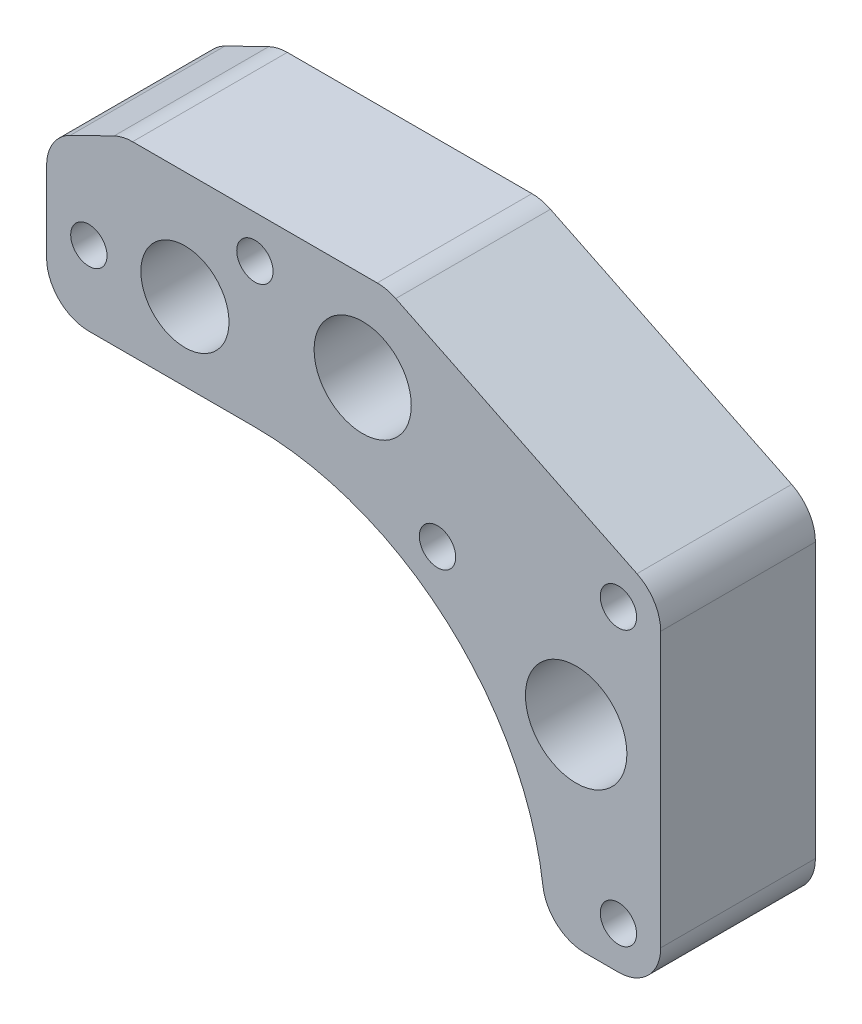
SolidWorks part; units mm, degrees
material "ABS"
ref_plane "前视基准面" through (0, 0, 0) normal (0, 0, 1) x (1, 0, 0)
ref_plane "上视基准面" through (0, 0, 0) normal (0, 1, 0) x (1, 0, 0)
ref_plane "右视基准面" through (0, 0, 0) normal (1, 0, 0) x (0, 0, -1)
other "Configuration Table"
sketch "草图1" plane through (0, 0, 0) normal (0, 0, 1) x (1, 0, 0)
  line L0 (0, 0) -> (0, 104) construction
  line L1 (0, 0) -> (-56, 0)
  line L2 (-56, 0) -> (-56, 56.65)
  line L4 (56, 56.65) -> (56, 0)
  line L5 (56, 0) -> (0, 0)
  line L6 (-56, 56.65) -> (-8.2819, 111.2395)
  line L7 (8.2819, 111.2395) -> (56, 56.65)
  arc A0 (34.35, 0) -> (-34.35, 0) centre (0, 0) ccw
  circle A1 centre (0, 104) radius 6
  arc A2 (8.2819, 111.2395) -> (-8.2819, 111.2395) centre (0, 104) ccw
  dimension "D1" = 68.7
  dimension "D3" = 12
  dimension "D7" = 5
  dimension "D2" = 104
  dimension "D4" = 112
  dimension "D5" = 56.65
  dimension "D6" = 56
extrude "凸台-拉伸1" add sketch "草图1" along normal blind 18.3
sketch "草图2" plane through (0, 0, 0) normal (0, 0, -1) x (-1, 0, 0)
  line L0 (56, 34.35) -> (0, 34.35)
  line L1 (56, 0) -> (56, 56.65) construction
  line L3 (56, 34.35) -> (56, 0)
  line L4 (56, 0) -> (34.35, 0)
  arc A0 (34.35, 0) -> (-34.35, 0) centre (0, 0) ccw construction
  arc A1 (34.35, 0) -> (0, 34.35) centre (0, 0) ccw
extrude "切除-拉伸1" cut sketch "草图2" against normal up to surface (18.3 mm away) up to face at (6, 104, 18.3)
sketch "草图3" plane through (0, 0, 0) normal (0, 0, -1) x (-1, 0, 0)
  line L0 (41, 34.35) -> (41, 59.35)
  line L1 (56, 34.35) -> (0, 34.35) construction
  line L2 (41, 59.35) -> (9.3178, 109.8462)
  line L3 (9.3178, 109.8462) -> (56, 56.65)
  line L4 (56, 56.65) -> (56, 34.35)
  line L5 (56, 34.35) -> (41, 34.35)
  arc A0 (8.2819, 111.2395) -> (-8.2819, 111.2395) centre (0, 104) ccw construction
  dimension "D1" = 15
  dimension "D2" = 25
extrude "切除-拉伸2" cut sketch "草图3" against normal up to surface (18.3 mm away) up to face at (5.183, 51.9192, 18.3)
sketch "草图4" plane through (0, 0, 18.3) normal (0, 0, 1) x (1, 0, 0)
  line L0 (-9.3178, 109.8462) -> (-8.855, 110.5838)
  line L1 (-56, 56.65) -> (-8.2819, 111.2395) construction
  line L10 (-56, 56.65) -> (-9.3178, 109.8462)
  line L11 (-9.3178, 109.8462) -> (-41, 59.35)
  line L12 (-41, 59.35) -> (-41, 34.35)
  line L13 (-41, 34.35) -> (0, 34.35)
  line L14 (34.35, 0) -> (56, 0)
  line L15 (56, 0) -> (56, 56.65)
  line L16 (56, 56.65) -> (8.2819, 111.2395)
  line L17 (-8.2819, 111.2395) -> (-56, 56.65)
  line L18 (-56, 56.65) -> (-9.3178, 109.8462)
  line L25 (-8.855, 110.5838) -> (-56, 56.65)
  arc A0 (8.2819, 111.2395) -> (-8.2819, 111.2395) centre (0, 104) ccw construction
  arc A3 (34.35, 0) -> (0, 34.35) centre (0, 0) ccw
  arc A4 (8.2819, 111.2395) -> (-8.2819, 111.2395) centre (0, 104) ccw
  dimension "D1" = 0
extrude "切除-拉伸3" cut sketch "草图4" against normal up to surface (18.3 mm away) up to face at (6, 104, 0)
fillet "圆角1" radius 2 1 edges at (-41, 34.35, 9.15)
sketch "草图5" plane through (0, 0, 0) normal (0, 0, -1) x (-1, 0, 0)
  line L1 (24.6418, 34.35) -> (24.6418, 85.4223)
  line L3 (39, 34.35) -> (0, 34.35) construction
  line L4 (24.6418, 34.35) -> (54.6418, 34.35)
  line L5 (54.6418, 34.35) -> (54.6418, 59.35)
  line L6 (54.6418, 59.35) -> (24.6418, 85.4223)
  line L8 (8.855, 110.5838) -> (41, 59.35) construction
  dimension "D1" = 24.6418
  dimension "D2" = 30
  dimension "D3" = 25
extrude "切除-拉伸4" cut sketch "草图5" against normal up to surface (18.3 mm away) up to face at (2.3195, 56.4573, 18.3)
sketch "草图6" plane through (0, 0, 18.3) normal (0, 0, 1) x (1, 0, 0)
  line L1 (54.3153, 37.4718) -> (15.6226, 56.3463) construction
  line L2 (-24.6418, 56.3463) -> (15.6226, 56.3463)
  line L3 (54.3153, 37.4718) -> (15.6226, 56.3463)
  line L4 (-24.6418, 85.4223) -> (-24.6418, 34.35) construction
  line L5 (-24.6418, 56.3463) -> (-24.6418, 119.4718)
  line L6 (-24.6418, 119.4718) -> (54.3153, 119.4718)
  line L7 (54.3153, 119.4718) -> (54.3153, 37.4718)
  line L8 (-24.6418, 34.35) -> (0, 34.35) construction
  dimension "D1" = 82
  dimension "D2" = 21.9963
extrude "切除-拉伸5" cut sketch "草图6" against normal up to surface (18.3 mm away) up to face at (6, 104, 0)
sketch "草图7" plane through (0, 0, 18.3) normal (0, 0, 1) x (1, 0, 0)
  line L0 (-15.6226, 56.3463) -> (-54.3153, 37.4718) construction
  line L1 (-15.6226, 56.3463) -> (-24.6418, 51.9467)
  line L2 (-24.6418, 56.3463) -> (-24.6418, 34.35) construction
  line L4 (-15.6226, 56.3463) -> (-24.6418, 56.3463)
  line L5 (-24.6418, 56.3463) -> (-24.6418, 51.9467)
extrude "切除-拉伸6" cut sketch "草图7" against normal blind 60
sketch "草图8" [suppressed] plane through (0, 0, 8) normal (0, 0, 1) x (1, 0, 0)
  line L0 (48, 0) -> (48, 65.802)
  line L1 (56, 0) -> (34.35, 0) construction
  line L2 (8.2819, 111.2395) -> (56, 56.65) construction
  line L3 (56, 56.65) -> (56, 0) construction
  line L4 (48, 65.802) -> (56, 56.65)
  line L5 (56, 56.65) -> (56, 0)
  line L6 (56, 0) -> (48, 0)
  dimension "D1" = 8
extrude "切除-拉伸7" [suppressed] cut sketch "草图8" against normal blind 74
sketch "草图9" plane through (0, 0, 18.3) normal (0, 0, 1) x (1, 0, 0)
  line L0 (48, 0) -> (48, 40.5524)
  line L1 (56, 0) -> (34.35, 0) construction
  line L2 (15.6226, 56.3463) -> (54.3153, 37.4718) construction
  line L3 (48, 40.5524) -> (56, 36.65)
  line L4 (56, 36.65) -> (56, 0)
  line L5 (56, 0) -> (48, 0)
  line L6 (56, 56.65) -> (56, 0) construction
  line L7 (15.6226, 56.3463) -> (54.3153, 37.4718) construction
  dimension "D1" = 8
extrude "切除-拉伸8" cut sketch "草图9" against normal blind 104
sketch "草图10" plane through (0, 0, 0) normal (0, 0, -1) x (-1, 0, 0)
  line L0 (-48, 0) -> (-34.35, 0) construction
  line L1 (-48, 40.5524) -> (-48, 0) construction
  line L2 (-48, 40.5524) -> (-15.6226, 56.3463) construction
  line L3 (0, 56.3463) -> (0, 51.3463) construction
  line L4 (-15.6226, 56.3463) -> (15.6226, 56.3463) construction
  line L5 (19.6418, 43.1483) -> (24.6418, 43.1483) construction
  line L6 (24.6418, 51.9467) -> (24.6418, 34.35) construction
  line L7 (0, 0) -> (-31.8113, 48.4494) construction
  circle A0 centre (-43, 5) radius 2.15
  circle A1 centre (-43, 37.4283) radius 2.15
  circle A2 centre (0, 51.3463) radius 2.15
  circle A3 centre (19.6418, 43.1483) radius 2.15
  circle A4 centre (-21.5974, 32.8934) radius 2.15
  arc A6 (0, 34.35) -> (-34.35, 0) centre (0, 0) ccw construction
  dimension "D1" = 4.3
  dimension "D2" = 5
  dimension "D3" = 5
  dimension "D4" = 5
  dimension "D5" = 5
  dimension "D6" = 5
  dimension "D7" = 5
  dimension "D8" = 5
extrude "切除-拉伸9" cut sketch "草图10" against normal blind 144
sketch "草图11" [suppressed] plane through (0, 0, 0) normal (0, 0, -1) x (-1, 0, 0)
  circle A0 centre (-43, 5) radius 2.15 construction
  circle A1 centre (-43, 37.4283) radius 2.15 construction
  circle A2 centre (-21.4019, 33.0209) radius 2.15 construction
  circle A3 centre (19.6418, 43.1483) radius 2.15 construction
  circle A4 centre (0, 51.65) radius 2.15 construction
  circle A5 centre (-43, 5) radius 2.15 construction
  circle A6 centre (-43, 37.4283) radius 2.15 construction
  circle A7 centre (-21.4019, 33.0209) radius 2.15 construction
  circle A8 centre (19.6418, 43.1483) radius 2.15 construction
  circle A9 centre (0, 51.65) radius 2.15 construction
  circle A10 centre (-43, 5) radius 2.025
  circle A11 centre (-43, 37.4283) radius 2.025
  circle A12 centre (-21.4019, 33.0209) radius 2.025
  circle A13 centre (0, 51.65) radius 2.025
  circle A14 centre (19.6418, 43.1483) radius 2.025
  dimension "D1" = 4.05
extrude "切除-拉伸10" [suppressed] cut sketch "草图11" against normal blind 144
fillet "圆角2" radius 5 7 edges at (-15.6226, 56.3463, 9.15) (-24.6418, 51.9467, 9.15) (-24.6418, 34.35, 9.15) (34.35, 0, 9.15) (48, 0, 9.15) (15.6226, 56.3463, 9.15) (48, 40.5524, 9.15)
sketch "草图13" plane through (0, 0, 0) normal (0, 0, -1) x (-1, 0, 0)
  line L3 (-45.1921, 41.9221) -> (-16.6602, 55.8401) construction
  line L5 (19.6418, 34.35) -> (0, 34.35) construction
  line L8 (-48, 37.4283) -> (-48, 5) construction
  circle A2 centre (-38, 22.8675) radius 6
  circle A3 centre (-12.7474, 45.7908) radius 5.7474
  circle A4 centre (8.2788, 43.563) radius 5.213
  circle A6 centre (0, 51.3463) radius 2.15 construction
  circle A8 centre (-21.5974, 32.8934) radius 2.15 construction
  circle A12 centre (19.6418, 43.1483) radius 2.15 construction
  arc A14 (0, 34.35) -> (-34.0716, 4.3647) centre (0, 0) ccw construction
  dimension "D1" = 5
  dimension "D2" = 7
  dimension "D3" = 5
  dimension "D4" = 4
  dimension "D5" = 4
  dimension "D6" = 4
  dimension "D7" = 4
  dimension "D8" = 4
  dimension "D9" = 12
extrude "切除-拉伸11" cut sketch "草图13" against normal blind 70
fillet "圆角3" [suppressed] radius 5
sketch "草图14" [suppressed] plane through (0, 0, 0) normal (0, 0, -1) x (-1, 0, 0)
  line L0 (-43, 37.4283) -> (0, 51.65) construction
  line L1 (0, 51.65) -> (0, 104) construction
  line L2 (-11.2585, 95.6786) -> (-40, 62.7984)
  line L3 (-40, 62.7984) -> (-40, 44.7402)
  line L4 (-40, 44.7402) -> (-6, 55.9852)
  line L5 (-6, 55.9852) -> (-6, 91.3509)
  line L6 (-48, 63.9247) -> (-48, 5) construction
  line L7 (-8.2819, 111.2395) -> (-46.7645, 67.2154) construction
  line L8 (6, 91.3509) -> (6, 55.5909)
  line L9 (6, 55.5909) -> (16.6418, 50.9848)
  line L10 (16.6418, 50.9848) -> (16.6418, 83.1204)
  line L11 (16.6418, 83.1204) -> (9.809, 94.0108)
  line L12 (0, 51.65) -> (19.6418, 43.1483) construction
  line L13 (9.0654, 110.2485) -> (23.8772, 86.641) construction
  line L14 (24.6418, 83.9837) -> (24.6418, 39.35) construction
  arc A2 (6, 91.3509) -> (9.809, 94.0108) centre (0, 104) ccw
  arc A3 (-11.2585, 95.6786) -> (-6, 91.3509) centre (0, 104) ccw
  dimension "D1" = 14
  dimension "D2" = 12
  dimension "D3" = 12
  dimension "D4" = 8
  dimension "D5" = 8
  dimension "D6" = 6
  dimension "D7" = 6
  dimension "D8" = 8
  dimension "D9" = 8
extrude "切除-拉伸12" [suppressed] cut sketch "草图14" against normal blind 70
fillet "圆角4" [suppressed] radius 4
delete or keep bodies "实体-删除/保留 1" type delete bodies bodies 119
